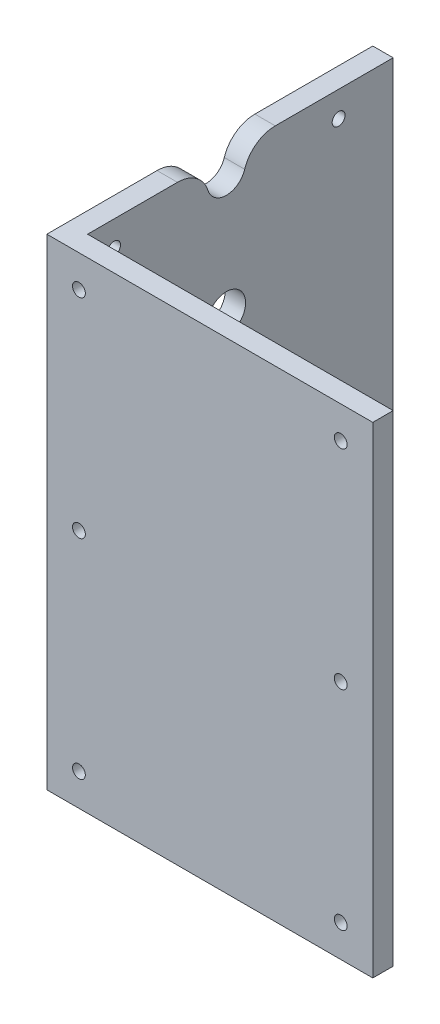
SolidWorks part; units mm, degrees
ref_plane "Alzado" through (0, 0, 0) normal (0, 0, 1) x (1, 0, 0)
ref_plane "Planta" through (0, 0, 0) normal (0, 1, 0) x (1, 0, 0)
ref_plane "Vista lateral" through (0, 0, 0) normal (1, 0, 0) x (0, 0, -1)
sketch "Croquis1" plane through (0, 0, 0) normal (0, 1, 0) x (1, 0, 0)
  line L0 (0, 101.6) -> (0, 0)
  line L1 (0, 0) -> (101.6, 0)
  line L6 (6.35, 101.6) -> (6.35, 6.35)
  line L7 (6.35, 6.35) -> (101.6, 6.35)
  line L8 (0, 101.6) -> (6.35, 101.6)
  line L9 (101.6, 6.35) -> (101.6, 0)
  dimension "D1" = 101.6
  dimension "D2" = 6.35
extrude "Saliente-Extruir1" add sketch "Croquis1" along normal blind 150
sketch "Croquis2" plane through (0, 0, 0) normal (-1, 0, 0) x (0, 0, 1)
  line L0 (-49.6, 150) -> (-49.6, 0) construction
  line L1 (-101.6, 150) -> (0, 150) construction
  line L2 (-101.6, 0) -> (0, 0) construction
  line L3 (-101.6, 142) -> (0, 142) construction
  line L4 (-101.6, 150) -> (-101.6, 0) construction
  line L5 (0, 150) -> (0, 0) construction
  line L6 (0, 0) -> (20, 0) construction
  line L7 (20, 0) -> (20, 150) construction
  line L8 (20, 150) -> (0, 150) construction
  line L9 (0, 150) -> (0, 0) construction
  line L10 (52, 59.96) -> (-20, 59.96) construction
  line L11 (-20, 59.96) -> (-20, -86.8957) construction
  line L12 (-20, -86.8957) -> (52, -86.8957) construction
  line L13 (52, -86.8957) -> (52, 59.96) construction
  line L14 (-6.35, 0) -> (-6.35, 150) construction
  circle A0 centre (-84.6, 142) radius 2
  circle A1 centre (-14.6, 142) radius 2
  circle A2 centre (-49.6, 59.96) radius 11
  circle A3 centre (-49.6, 7.71) radius 1.5
  circle A4 centre (-49.6, 144.86) radius 6
  circle A5 centre (-49.6, 106.86) radius 6
  circle A6 centre (-49.6, 59.96) radius 101.6 construction
  dimension "D4" = 4
  dimension "D5" = 22
  dimension "D7" = 3
  dimension "D10" = 12
  dimension "D12" = 12
  dimension "D14" = 203.2
  dimension "D1" = 8
  dimension "D2" = 49.6
  dimension "D3" = 35
  dimension "D6" = 82.04
  dimension "D8" = 52.25
  dimension "D9" = 84.9
  dimension "D11" = 46.9
  dimension "D13" = 20
  dimension "D15" = 72
  dimension "D16" = 6.35
extrude "Cortar-Extruir1" cut sketch "Croquis2" against normal through all
fillet "Redondeo1" radius 10 2 edges at (3.175, 150, -52.6952) (3.175, 150, -46.5048)
sketch "Croquis3" plane through (0, 0, 0) normal (-1, 0, 0) x (0, 0, 1)
  circle A0 centre (-49.6, 59.96) radius 12.5
  dimension "D1" = 25
extrude "Cortar-Extruir2" cut sketch "Croquis3" against normal blind 1.5
sketch "Croquis4" plane through (0, 0, 0) normal (-1, 0, 0) x (0, 0, 1)
  line L0 (-49.6, 59.96) -> (-49.6, 78.61) construction
  line L1 (-49.6, 59.96) -> (0, 59.96) construction
  line L2 (0, 150) -> (0, 0) construction
  circle A0 centre (-49.6, 78.61) radius 2
  circle A1 centre (-49.6, 41.31) radius 2
  circle A2 centre (-49.6, 59.96) radius 13.5 construction
  circle A3 centre (-34.6, 59.96) radius 1.5
  circle A4 centre (-57.1, 46.9696) radius 1.5
  circle A5 centre (-57.1, 72.9504) radius 1.5
  circle A6 centre (-49.6, 59.96) radius 20 construction
  circle A7 centre (-26.1, 59.96) radius 3.5 construction
  circle A8 centre (-26.1, 59.96) radius 1.5
  circle A9 centre (-61.35, 39.6084) radius 1.5
  circle A10 centre (-61.35, 80.3116) radius 1.5
  point P19 (-49.6, 59.96)
  point P27 (-49.6, 59.96)
  dimension "D2" = 4
  dimension "D3" = 27
  dimension "D4" = 3
  dimension "D7" = 40
  dimension "D8" = 7
  dimension "D9" = 3
  dimension "D1" = 18.65
  dimension "D5" = 15
  dimension "D6" = 3
  dimension "D10" = 3
extrude "Cortar-Extruir3" cut sketch "Croquis4" against normal through all
sketch "Croquis6" plane through (0, 0, 0) normal (0, 0, 1) x (1, 0, 0)
  line L0 (91.6, 150) -> (91.6, 0) construction
  line L1 (0, 150) -> (101.6, 150) construction
  line L2 (0, 0) -> (101.6, 0) construction
  line L3 (101.6, 150) -> (101.6, 0) construction
  line L4 (91.6, 75) -> (0, 75) construction
  line L5 (0, 150) -> (0, 0) construction
  line L6 (50.8, 150) -> (50.8, 0) construction
  circle A0 centre (91.6, 140) radius 2
  circle A1 centre (91.6, 75) radius 2
  circle A2 centre (91.6, 10) radius 2
  circle A3 centre (10, 10) radius 2
  circle A4 centre (10, 75) radius 2
  circle A5 centre (10, 140) radius 2
  dimension "D3" = 4
  dimension "D1" = 10
  dimension "D2" = 10
extrude "Cortar-Extruir4" cut sketch "Croquis6" against normal through all
